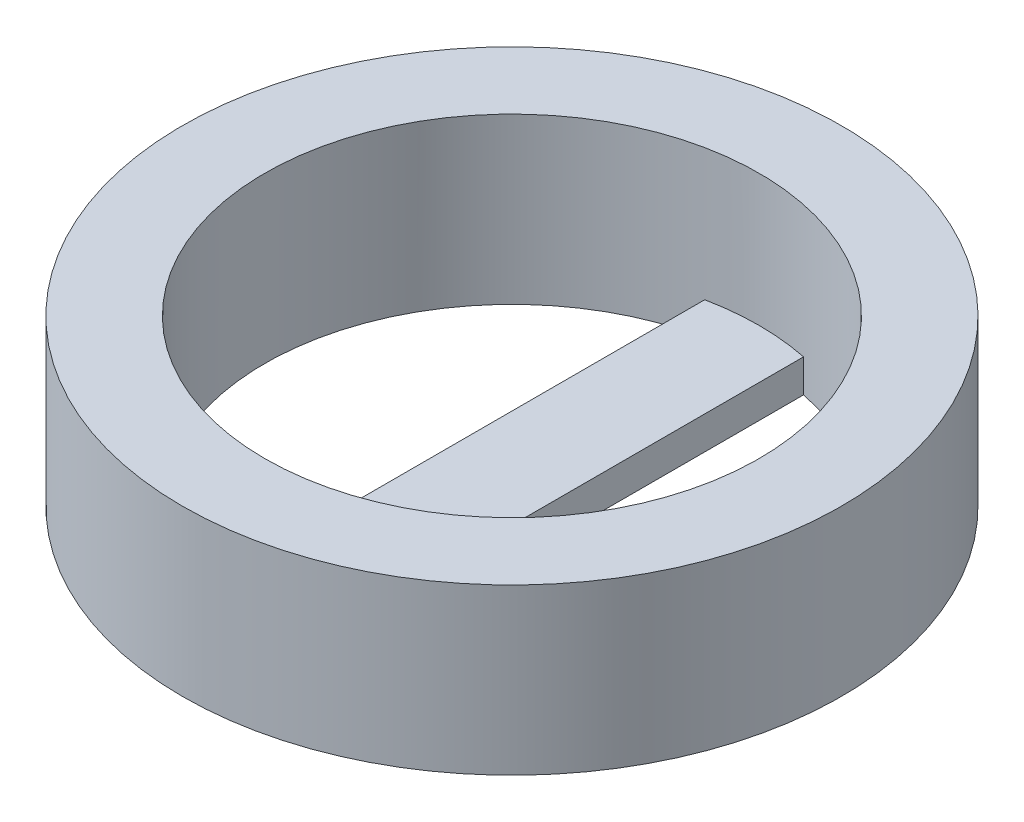
SolidWorks part; units mm, degrees
ref_plane "Front Plane" through (0, 0, 0) normal (0, 0, 1) x (1, 0, 0)
ref_plane "Top Plane" through (0, 0, 0) normal (0, 1, 0) x (1, 0, 0)
ref_plane "Right Plane" through (0, 0, 0) normal (1, 0, 0) x (0, 0, -1)
sketch "Sketch1" plane through (0, 0, 0) normal (0, 1, 0) x (1, 0, 0)
  circle A0 centre (0, 0) radius 10
  circle A1 centre (0, 0) radius 7.5
  dimension "D1" = 20
  dimension "D2" = 15
extrude "Boss-Extrude1" add sketch "Sketch1" along normal blind 5
sketch "Sketch2" plane through (0, 0, 0) normal (0, -1, 0) x (1, 0, 0)
  line L1 (-1.5, -7.5) -> (1.5, -7.5)
  line L2 (-1.5, -7.5) -> (-1.5, 7.5)
  line L3 (-1.5, 7.5) -> (1.5, 7.5)
  line L4 (1.5, -7.5) -> (1.5, 7.5)
  line L5 (-1.5, -7.5) -> (1.5, 7.5) construction
  line L6 (-1.5, 7.5) -> (1.5, -7.5) construction
  point P0 (0, 0)
  dimension "D1" = 15
  dimension "D2" = 3
extrude "Boss-Extrude2" add sketch "Sketch2" against normal blind 1
